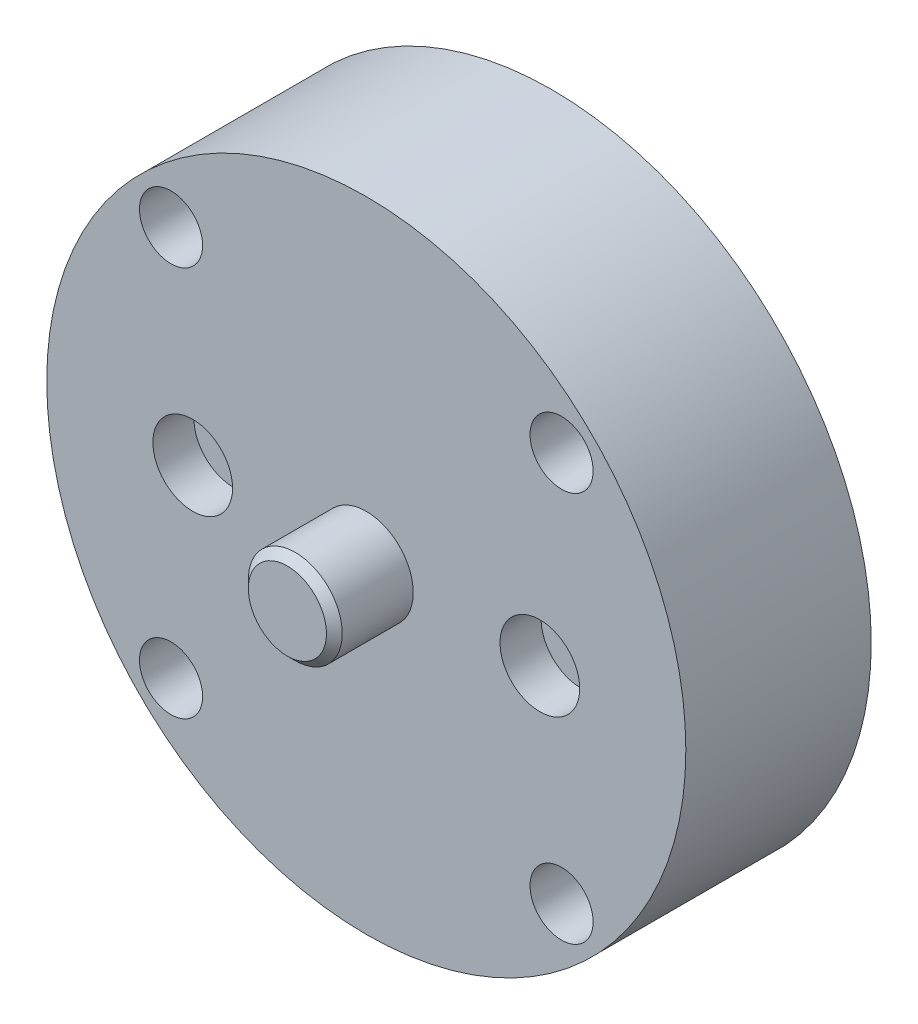
SolidWorks part; units mm, degrees
material "Polyetheretherketone (PEEK)"
ref_plane "Front Plane" through (0, 0, 0) normal (0, 0, 1) x (1, 0, 0)
ref_plane "Top Plane" through (0, 0, 0) normal (0, 1, 0) x (1, 0, 0)
ref_plane "Right Plane" through (0, 0, 0) normal (1, 0, 0) x (0, 0, -1)
ref_plane "Plane1" through (0, 0, 0) normal (0, -1, 0) x (1, 0, 0)
sketch "Sketch1" plane through (0, 0, 0) normal (0, -1, 0) x (1, 0, 0)
  line L0 (40.5, 23.5) -> (0, 23.5)
  line L1 (0, 23.5) -> (0, 0)
  line L2 (0, 0) -> (40.5, 0)
  line L3 (40.5, 0) -> (40.5, 23.5)
  line L4 (0, 23.5) -> (0, 0) construction
  dimension "D1" = 40.5
  dimension "D2" = 23.5
  dimension "D3" = 40.5
  dimension "D4" = 23.5
revolve "Revolve1" add sketch "Sketch1" angle 360 about L4
sketch "Sketch2" plane through (0, 0, 23.5) normal (0, 0, 1) x (1, 0, 0)
  circle A0 centre (0, 0) radius 5.95
  dimension "D1" = 11.9
extrude "Boss-Extrude1" add sketch "Sketch2" along normal blind 10
hole_wizard "Hole1" positions "Sketch4" profile "Sketch3" legacy
sketch "Sketch4" plane through (0, 0, 23.5) normal (0, 0, 1) x (1, 0, 0)
  point P0 (22, 0)
  point P1 (-22, 0)
  dimension "D1" = 22
  dimension "D2" = 22
sketch "Sketch3" plane through (22, 0, 23.5) normal (1, 0, 0) x (0, -1, 0)
  line L0 (0, 0) -> (0, 5.2)
  line L1 (0, 5.2) -> (5.05, 5.2)
  line L2 (5.05, 5.2) -> (5.05, 0)
  line L3 (5.05, 0) -> (0, 0)
  line L4 (0, 110) -> (0, -10) construction
  dimension "Diameter" = 10.1
  dimension "Depth" = 5.2
hole_wizard "CBORE for M4 Hex Head Machine Screw1" positions "Sketch6" profile "Sketch5" counterbore size "M4" standard "ANSI Metric"
sketch "Sketch6" plane through (0, 0, 23.5) normal (0, 0, 1) x (1, 0, 0)
  point P0 (24.7487, 24.7487)
  point P1 (-24.7487, 24.7487)
  point P2 (24.7487, -24.7487)
  point P3 (-24.7487, -24.7487)
  dimension "D1" = 24.7487
  dimension "D2" = 24.7487
  dimension "D3" = 24.7487
  dimension "D4" = 24.7487
  dimension "D5" = 24.7487
  dimension "D6" = 24.7487
  dimension "D7" = 24.7487
  dimension "D8" = 24.7487
sketch "Sketch5" plane through (24.7487, 24.7487, 23.5) normal (1, 0, 0) x (0, -1, 0)
  line L0 (0, 0) -> (0, 23.5)
  line L1 (0, 23.5) -> (2.25, 23.5)
  line L3 (2.25, 23.5) -> (2.25, 6)
  line L4 (2.25, 6) -> (4, 6)
  line L5 (4, 6) -> (4, 0)
  line L7 (4, 0) -> (0, 0)
  line L11 (0, -6.35) -> (0, 107.95) construction
  dimension "Thru Hole Dia." = 4.5
  dimension "Thru Hole Depth" = 23.5
  dimension "C'Bore Dia." = 8
  dimension "C'Bore Depth" = 6
chamfer "Chamfer1" distance 1 angle 45 1 edges at (5.95, 0, 33.5)
